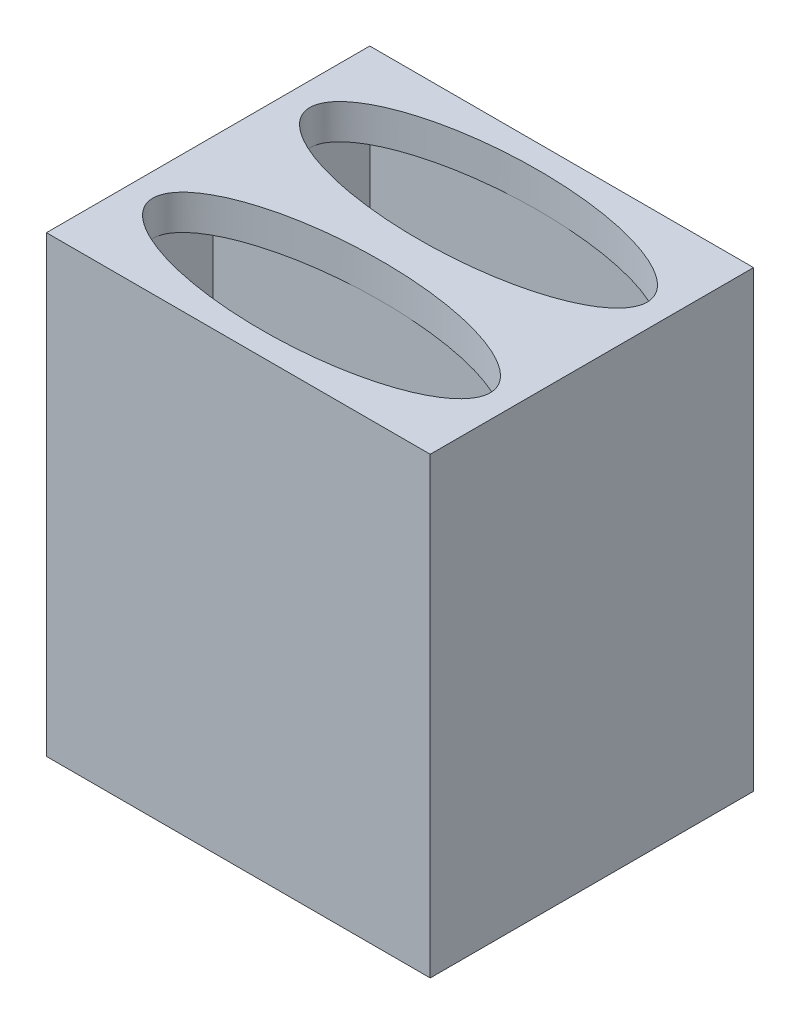
SolidWorks part; units mm, degrees
ref_plane "Front Plane" through (0, 0, 0) normal (0, 0, 1) x (1, 0, 0)
ref_plane "Top Plane" through (0, 0, 0) normal (0, 1, 0) x (1, 0, 0)
ref_plane "Right Plane" through (0, 0, 0) normal (1, 0, 0) x (0, 0, -1)
sketch "草图1" plane through (0, 0, 0) normal (0, 1, 0) x (1, 0, 0)
  line L0 (-16.5, -7.15) -> (-16.5, 7.15)
  line L1 (-14.5, -5.15) -> (14.5, -5.15)
  line L2 (-14.5, -5.15) -> (-14.5, 5.15)
  line L3 (-14.5, 5.15) -> (14.5, 5.15)
  line L4 (14.5, -5.15) -> (14.5, 5.15)
  line L5 (-14.5, -5.15) -> (14.5, 5.15) construction
  line L6 (-14.5, 5.15) -> (14.5, -5.15) construction
  line L7 (-16.5, 7.15) -> (16.5, 7.15)
  line L8 (16.5, -7.15) -> (16.5, 7.15)
  line L9 (-16.5, -7.15) -> (16.5, -7.15)
  point P0 (0, 0)
  dimension "D1" = 10.3
  dimension "D2" = 29
  dimension "D3" = 2
extrude "凸台-拉伸2" add sketch "草图1" along normal blind 36
sketch "草图2" plane through (0, 36, 0) normal (0, 1, 0) x (1, 0, 0)
  line L0 (14.5, -5.15) -> (14.5, 5.15) construction
  line L1 (16.5, 7.15) -> (-16.5, 7.15)
  line L2 (16.5, 7.15) -> (16.5, -7.15)
  line L3 (16.5, -7.15) -> (-16.5, -7.15)
  line L4 (-16.5, 7.15) -> (-16.5, -7.15)
  line L5 (-14.5, -5.15) -> (14.5, -5.15) construction
  ellipse E0 centre (0, 0) end of major axis (14.5, 0) minor radius 5.15
extrude "凸台-拉伸3" add sketch "草图2" along normal blind 3
pattern_linear "阵列(线性)1" count 2 spacing 13.5 along (0, 0, -1) of "凸台-拉伸2", "凸台-拉伸3"
